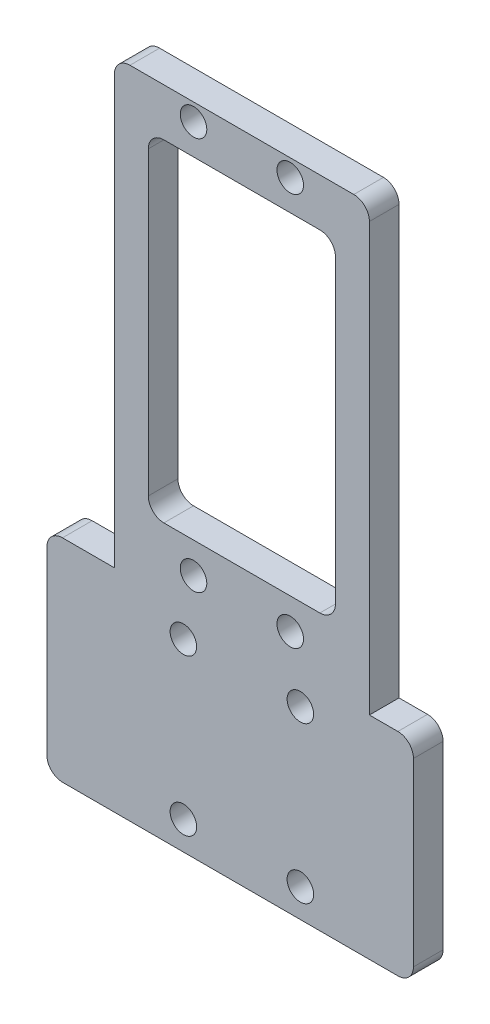
SolidWorks part; units mm, degrees
ref_plane "Front Plane" through (0, 0, 0) normal (0, 0, 1) x (1, 0, 0)
ref_plane "Top Plane" through (0, 0, 0) normal (0, 1, 0) x (1, 0, 0)
ref_plane "Right Plane" through (0, 0, 0) normal (1, 0, 0) x (0, 0, -1)
sketch "Sketch1" plane through (0, 0, 0) normal (0, 0, 1) x (1, 0, 0)
  line L0 (22.8792, 70.3) -> (11.8208, 70.3) construction
  line L1 (3, 70.3) -> (31.7, 70.3)
  line L2 (-7.65, -11.6411) -> (-7.65, 11.5)
  line L3 (40.7977, 13.5) -> (44.7833, 13.5) construction
  line L4 (27.35, 42.9) -> (19.1646, 42.9) construction
  line L5 (17.35, -13.6411) -> (17.35, -22.4735) construction
  line L6 (23.55, 68.1) -> (11.15, 68.1) construction
  line L7 (7.35, 64.1908) -> (27.35, 64.1908)
  line L8 (1, 68.3) -> (1, 13.5)
  line L9 (3, -13.6411) -> (31.7, -13.6411)
  line L10 (33.7, 13.5) -> (33.7, 68.3)
  line L12 (5.35, 62.1908) -> (5.35, 23.654)
  line L13 (7.35, 21.654) -> (27.35, 21.654)
  line L14 (29.35, 62.1908) -> (29.35, 23.654)
  line L15 (39.35, 11.5) -> (39.35, -11.6411)
  line L16 (3, -13.6411) -> (-5.65, -13.6411)
  line L17 (-5.65, 13.5) -> (1, 13.5)
  line L18 (37.35, 13.5) -> (33.7, 13.5)
  line L19 (37.35, -13.6411) -> (31.7, -13.6411)
  arc A0 (27.35, 21.654) -> (29.35, 23.654) centre (27.35, 23.654) ccw
  arc A1 (5.35, 23.654) -> (7.35, 21.654) centre (7.35, 23.654) ccw
  circle A2 centre (11.15, 17.7) radius 1.7
  circle A4 centre (9.85, 10) radius 1.7
  circle A5 centre (24.85, 10) radius 1.7
  circle A6 centre (9.85, -10) radius 1.7
  circle A7 centre (24.85, -10) radius 1.7
  circle A8 centre (23.55, 17.7) radius 1.7
  arc A10 (1, 68.3) -> (3, 70.3) centre (3, 68.3) cw
  arc A11 (33.7, 68.3) -> (31.7, 70.3) centre (31.7, 68.3) ccw
  circle A12 centre (23.55, 68.1) radius 1.7
  circle A13 centre (11.15, 68.1) radius 1.7
  arc A14 (27.35, 64.1908) -> (29.35, 62.1908) centre (27.35, 62.1908) cw
  arc A15 (7.35, 64.1908) -> (5.35, 62.1908) centre (7.35, 62.1908) ccw
  arc A16 (39.35, 11.5) -> (37.35, 13.5) centre (37.35, 11.5) ccw
  arc A17 (-7.65, 11.5) -> (-5.65, 13.5) centre (-5.65, 11.5) cw
  arc A18 (-7.65, -11.6411) -> (-5.65, -13.6411) centre (-5.65, -11.6411) ccw
  arc A19 (39.35, -11.6411) -> (37.35, -13.6411) centre (37.35, -11.6411) cw
  point P11 (39.35, 13.5)
  point P37 (17.35, 68.1)
  point P38 (17.35, 64.1908)
  point P57 (-7.65, 13.5)
  dimension "D6" = 3.4
  dimension "D7" = 3.4
  dimension "D8" = 3.4
  dimension "D9" = 3.4
  dimension "D2" = 3.4
  dimension "D10" = 3.4
  dimension "D11" = 2
  dimension "D13" = 2
  dimension "D3" = 20
  dimension "D4" = 20
  dimension "D5" = 15
  dimension "D12" = 12
  dimension "D14" = 25
  dimension "D15" = 22
extrude "Boss-Extrude1" add sketch "Sketch1" along normal blind 3.8
